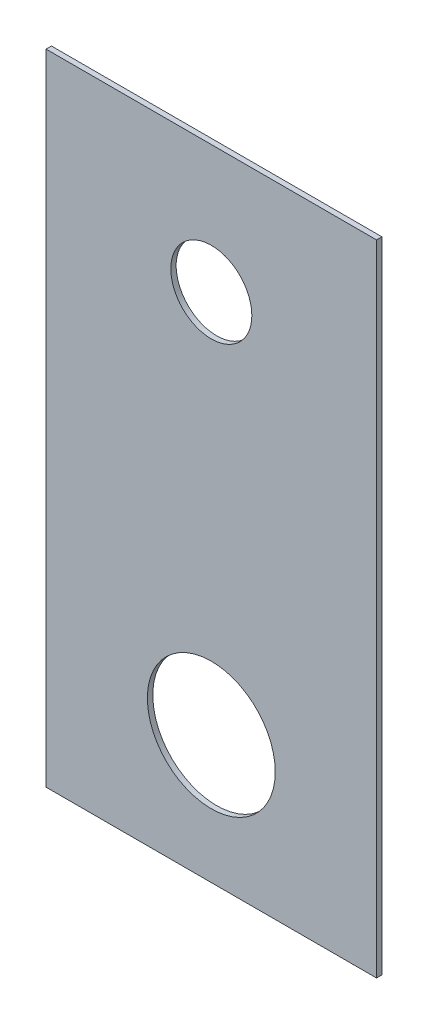
SolidWorks part; units mm, degrees
material "Ti-6Al-4VSolution treated and aged (SS)"
ref_plane "Front Plane" through (0, 0, 0) normal (0, 0, 1) x (1, 0, 0)
ref_plane "Top Plane" through (0, 0, 0) normal (0, 1, 0) x (1, 0, 0)
ref_plane "Right Plane" through (0, 0, 0) normal (1, 0, 0) x (0, 0, -1)
sketch "Sketch1" plane through (0, 0, 0) normal (0, 0, 1) x (1, 0, 0)
  line L0 (32.8295, 164.3596) -> (32.8295, -87.6001) construction
  line L1 (0, 0) -> (65.659, 0)
  line L2 (0, 0) -> (0, 127)
  line L3 (0, 127) -> (65.659, 127)
  line L4 (65.659, 0) -> (65.659, 127)
  circle A0 centre (32.8295, 101.6) radius 8.0518
  circle A1 centre (32.8295, 25.4) radius 12.7
  point P11 (32.8295, 0)
  dimension "D3" = 16.1036
  dimension "D4" = 25.4
  dimension "D1" = 127
  dimension "D2" = 65.659
  dimension "D5" = 76.2
  dimension "D6" = 25.4
extrude "Boss-Extrude1" add sketch "Sketch1" along normal blind 1.0683
equation "\"E\"= 15200000'psi elastic"
equation "\"Sy\"= 120000'psi yield"
equation "\"Fs\"= 5'Factor of safety"
equation "\"Ltot\"= 5'in, length of link"
equation "\"width total\"= 2.585'width of total piece"
equation "\"W\"= 800'lbf load per side"
equation "\"SyFs\"= ( \"Sy\" / \"Fs\" )'max stress w safety factor"
equation "\"D1@Sketch1\"=\"Ltot\""
equation "\"diam hole 1\"= 1'in diam of attached bar"
equation "\"diam hole brack\"= 0.634'in diam of bracket bar"
equation "\"width side\"= ( \"width total\" - \"diam hole 1\" ) / 2'width of bracket per side"
equation "\"D2@Sketch1\"=\"width total\""
equation "\"D3@Sketch1\"=\"diam hole brack\""
equation "\"D4@Sketch1\"=\"diam hole 1\""
equation "\"depth\"= ( \"W\" / ( \"SyFs\" * \"width side\" ) )'depth of link"
equation "\"D1@Boss-Extrude1\"=\"depth\""
